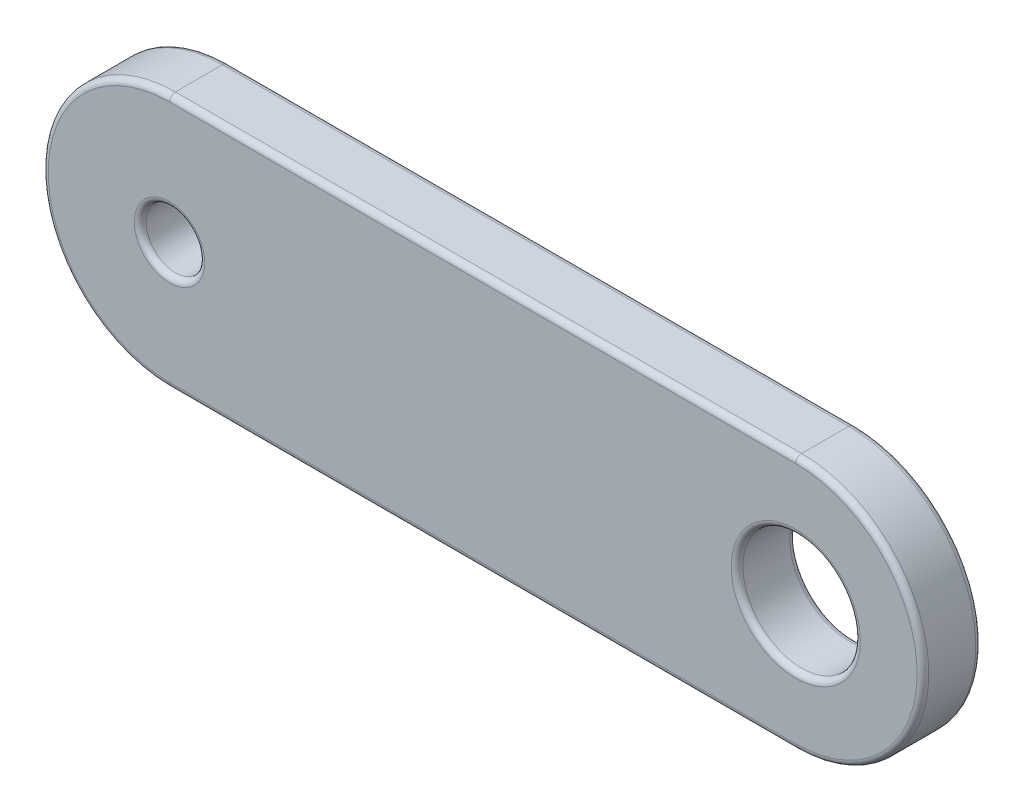
SolidWorks part; units mm, degrees
ref_plane "Front Plane" through (0, 0, 0) normal (0, 0, 1) x (1, 0, 0)
ref_plane "Top Plane" through (0, 0, 0) normal (0, 1, 0) x (1, 0, 0)
ref_plane "Right Plane" through (0, 0, 0) normal (1, 0, 0) x (0, 0, -1)
sketch "Sketch1" plane through (0, 0, 0) normal (0, 0, 1) x (1, 0, 0)
  line L0 (-8, 0) -> (8, 0) construction
  line L1 (-8, 3.25) -> (8, 3.25)
  line L2 (-8, -3.25) -> (8, -3.25)
  arc A0 (-8, 3.25) -> (-8, -3.25) centre (-8, 0) ccw
  arc A1 (8, -3.25) -> (8, 3.25) centre (8, 0) ccw
  circle A2 centre (-8, 0) radius 0.75
  circle A3 centre (8, 0) radius 1.5
  point P2 (0, 0)
  dimension "D3" = 3
  dimension "D4" = 1.5
  dimension "D1" = 16
  dimension "D2" = 6.5
extrude "Boss-Extrude1" add sketch "Sketch1" along normal mid plane 1.5
fillet "Fillet1" radius 0.15 12 edges at (9.5, 0, -0.75) (-7.25, 0, -0.75) (0, -3.25, -0.75) (11.25, 0, -0.75) (0, 3.25, -0.75) (-11.25, 0, -0.75) (9.5, 0, 0.75) (0, 3.25, 0.75) (11.25, 0, 0.75) (0, -3.25, 0.75) (-11.25, 0, 0.75) (-7.25, 0, 0.75)
